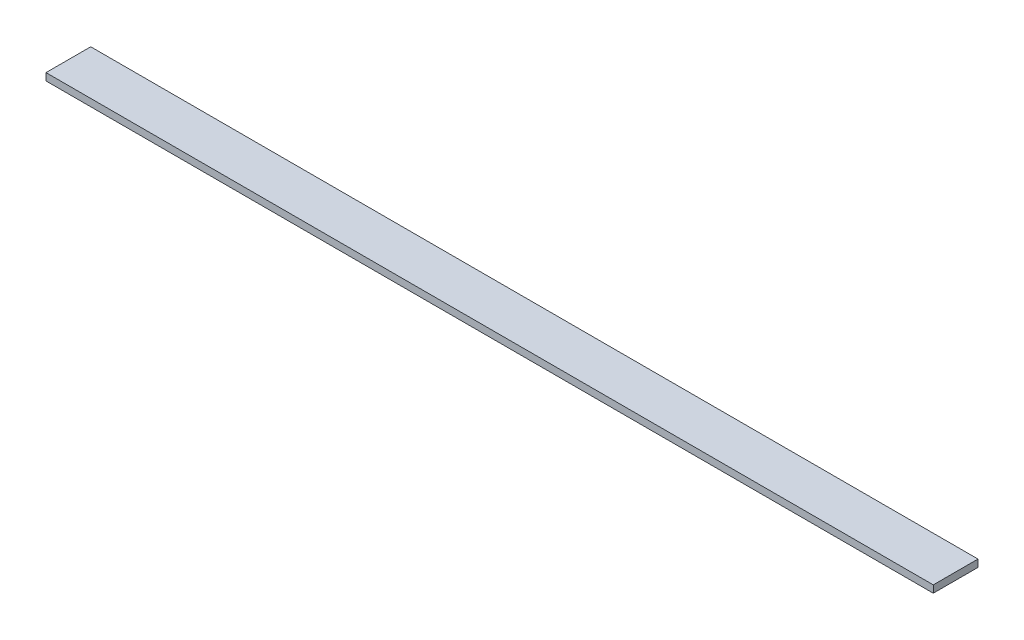
SolidWorks part; units mm, degrees
material "Pine"
ref_plane "Front Plane" through (0, 0, 0) normal (0, 0, 1) x (1, 0, 0)
ref_plane "Top Plane" through (0, 0, 0) normal (0, 1, 0) x (1, 0, 0)
ref_plane "Right Plane" through (0, 0, 0) normal (1, 0, 0) x (0, 0, -1)
sketch "Sketch1" plane through (0, 0, 0) normal (0, 1, 0) x (1, 0, 0)
  line L1 (-442.7289, 151.0393) -> (4218.1711, 151.0393)
  line L2 (-442.7289, 151.0393) -> (-442.7289, -83.9107)
  line L3 (-442.7289, -83.9107) -> (4218.1711, -83.9107)
  line L4 (4218.1711, 151.0393) -> (4218.1711, -83.9107)
  dimension "D1" = 234.95
  dimension "D2" = 4660.9
extrude "Boss-Extrude1" add sketch "Sketch1" along normal blind 38.1 contours L3 L4 L1 L2
